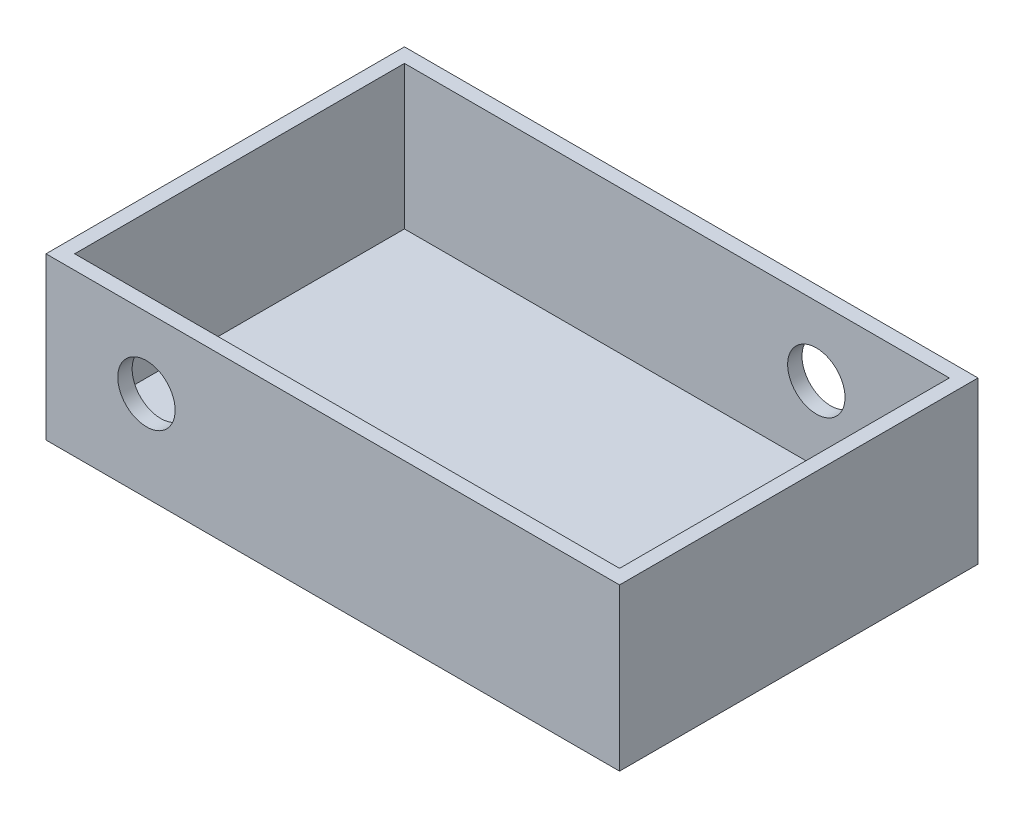
SolidWorks part; units mm, degrees
ref_plane "Front" through (0, 0, 0) normal (0, 0, 1) x (1, 0, 0)
ref_plane "Top" through (0, 0, 0) normal (0, 1, 0) x (1, 0, 0)
ref_plane "Right" through (0, 0, 0) normal (1, 0, 0) x (0, 0, -1)
sketch "Sketch1" plane through (0, 0, 0) normal (0, 1, 0) x (1, 0, 0)
  line L1 (0, 0) -> (80, 0)
  line L2 (0, 0) -> (0, -50)
  line L3 (0, -50) -> (80, -50)
  line L4 (80, 0) -> (80, -50)
  dimension "D1" = 80
  dimension "D2" = 50
extrude "Boss-Extrude1" add sketch "Sketch1" along normal blind 2.5
sketch "Sketch2" plane through (0, 2.5, 0) normal (0, 1, 0) x (1, 0, 0)
  line L0 (2, -2) -> (2, -48)
  line L1 (0, 0) -> (80, 0)
  line L2 (0, 0) -> (0, -50)
  line L3 (0, -50) -> (80, -50)
  line L4 (80, 0) -> (80, -50)
  line L5 (2, -48) -> (78, -48)
  line L6 (78, -2) -> (78, -48)
  line L7 (2, -2) -> (78, -2)
  dimension "D1" = 2
extrude "Boss-Extrude2" add sketch "Sketch2" along normal blind 20
sketch "Sketch3" plane through (0, 0, 50) normal (0, 0, 1) x (1, 0, 0)
  circle A0 centre (14.0136, 12.6012) radius 4
  dimension "D1" = 8
extrude "Cut-Extrude1" cut sketch "Sketch3" against normal blind 20
sketch "Sketch4" plane through (0, 0, 2) normal (0, 0, 1) x (1, 0, 0)
  circle A0 centre (59.449, 12.8599) radius 4
  dimension "D1" = 8
extrude "Cut-Extrude2" cut sketch "Sketch4" against normal blind 20
